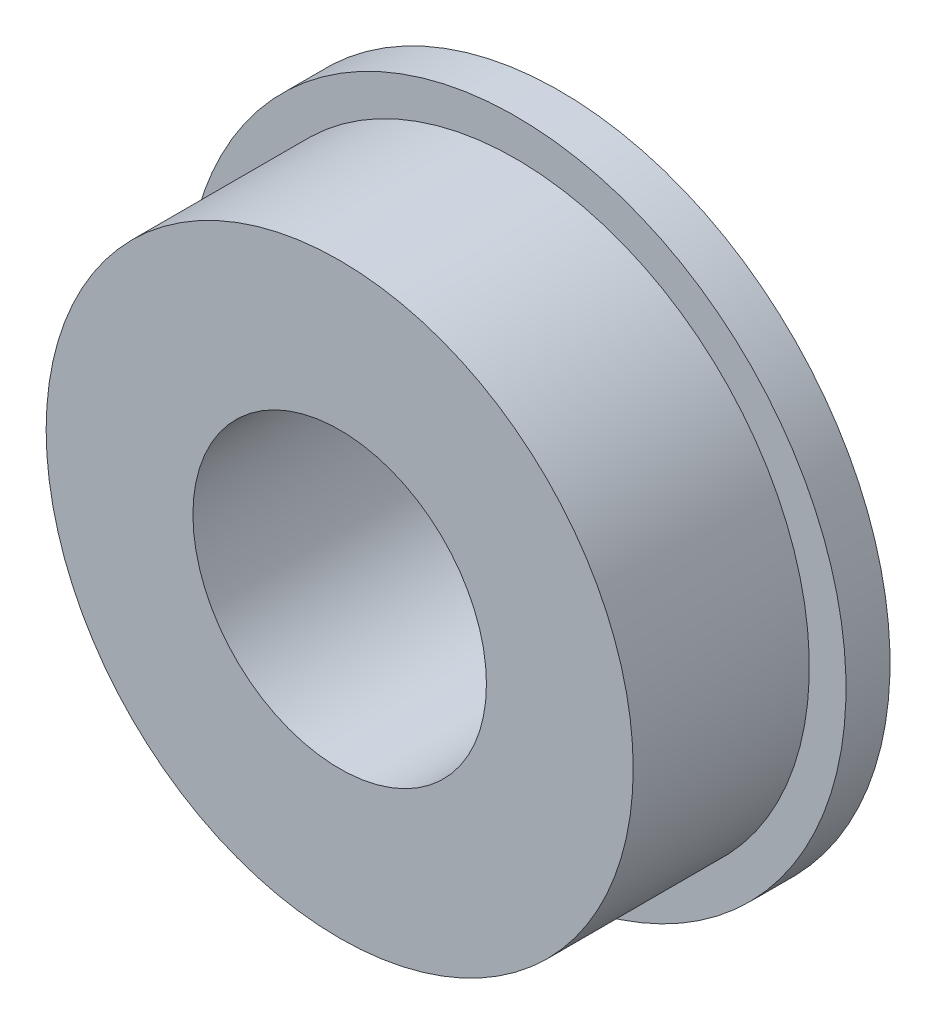
SolidWorks part; units mm, degrees
ref_plane "Front Plane" through (0, 0, 0) normal (0, 0, 1) x (1, 0, 0)
ref_plane "Top Plane" through (0, 0, 0) normal (0, 1, 0) x (1, 0, 0)
ref_plane "Right Plane" through (0, 0, 0) normal (1, 0, 0) x (0, 0, -1)
sketch "Sketch1" plane through (0, 0, 0) normal (0, 0, 1) x (1, 0, 0)
  circle A0 centre (0, 0) radius 4
  circle A1 centre (0, 0) radius 2
  dimension "D1" = 4
  dimension "D2" = 8
extrude "Boss-Extrude1" add sketch "Sketch1" along normal blind 3
sketch "Sketch2" plane through (0, 0, 0) normal (0, 0, -1) x (-1, 0, 0)
  circle A0 centre (0, 0) radius 4.5
  circle A1 centre (0, 0) radius 2 construction
  circle A2 centre (0, 0) radius 2
  dimension "D1" = 9
extrude "Boss-Extrude2" add sketch "Sketch2" against normal blind 0.6
